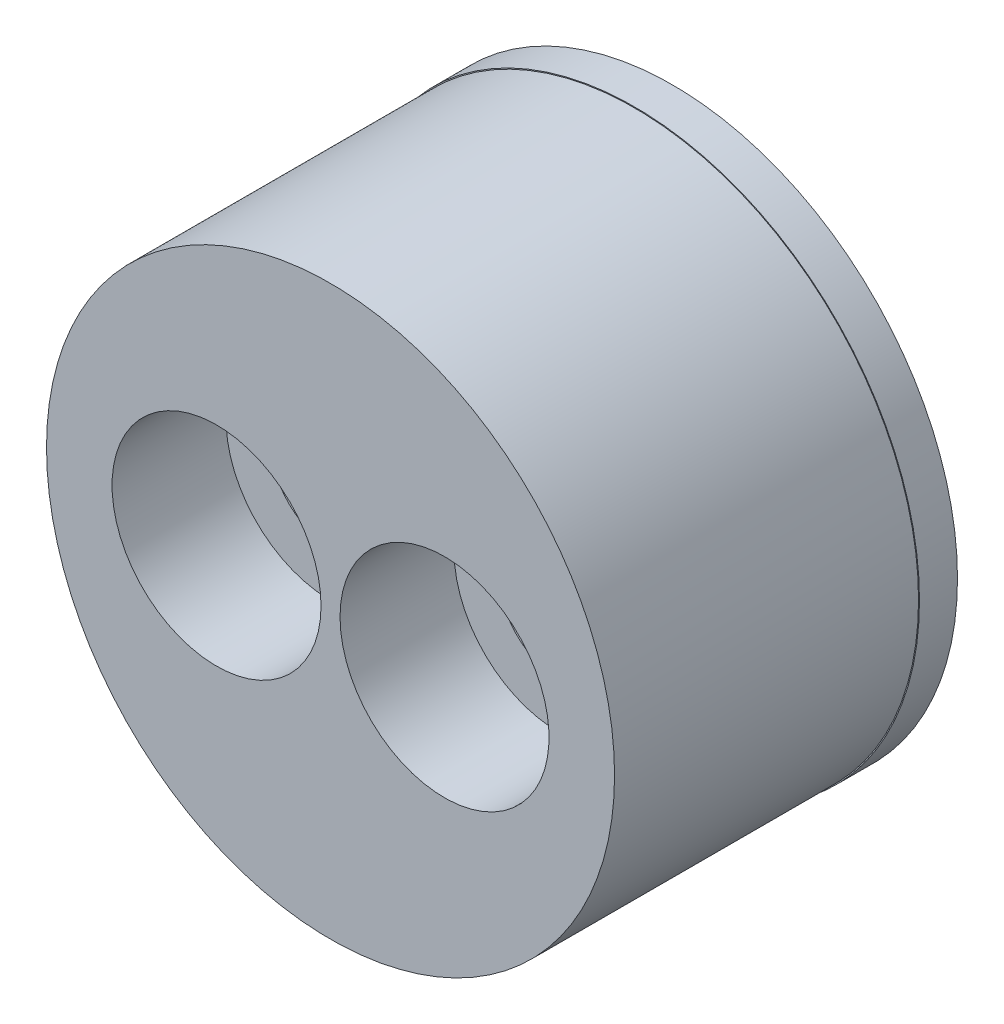
SolidWorks part; units mm, degrees
ref_plane "Front Plane" through (0, 0, 0) normal (0, 0, 1) x (1, 0, 0)
ref_plane "Top Plane" through (0, 0, 0) normal (0, 1, 0) x (1, 0, 0)
ref_plane "Right Plane" through (0, 0, 0) normal (1, 0, 0) x (0, 0, -1)
sketch "Sketch1" plane through (0, 0, 0) normal (0, 0, 1) x (1, 0, 0)
  circle A0 centre (0, 0) radius 7.5
  dimension "D1" = 15
extrude "Boss-Extrude1" add sketch "Sketch1" along normal blind 1
sketch "Sketch2" plane through (0, 0, 1) normal (0, 0, 1) x (1, 0, 0)
  circle A0 centre (0, 0) radius 7.475
  dimension "D1" = 14.95
extrude "Boss-Extrude2" add sketch "Sketch2" along normal blind 8
sketch "Sketch3" plane through (0, 0, 9) normal (0, 0, 1) x (1, 0, 0)
  line L0 (-11.5371, 0) -> (13.2308, 0) construction
  line L1 (0, -11.5371) -> (0, 10.948) construction
  circle A0 centre (-3, 0) radius 1.55
  circle A1 centre (3, 0) radius 1.55
  dimension "D1" = 3.1
  dimension "D2" = 3
extrude "Cut-Extrude1" cut sketch "Sketch3" against normal through all
sketch "Sketch4" plane through (0, 0, 9) normal (0, 0, 1) x (1, 0, 0)
  line L0 (0, -11.2671) -> (0, 10.8743) construction
  circle A0 centre (-3, 0) radius 2.75
  circle A1 centre (3, 0) radius 2.75
  dimension "D1" = 5.5
extrude "Cut-Extrude2" cut sketch "Sketch4" against normal blind 3
